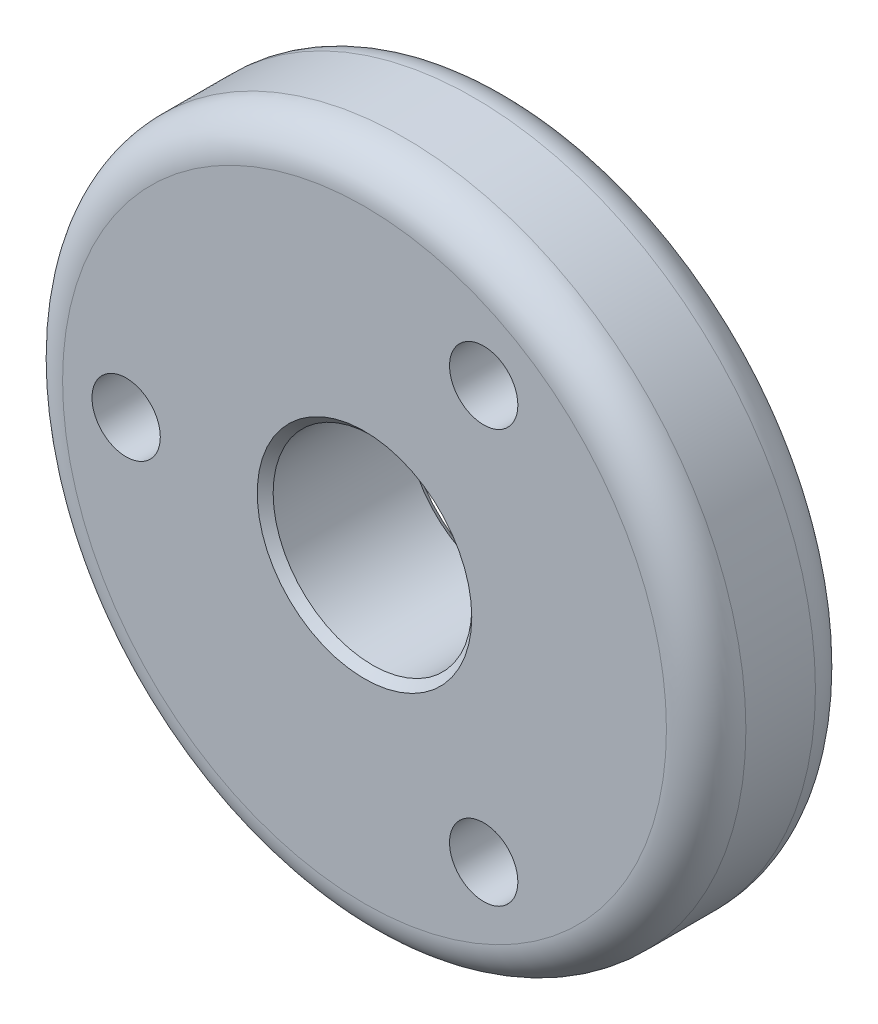
SolidWorks part; units mm, degrees
material "Alloy Steel"
ref_plane "Front Plane" through (0, 0, 0) normal (0, 0, 1) x (1, 0, 0)
ref_plane "Top Plane" through (0, 0, 0) normal (0, 1, 0) x (1, 0, 0)
ref_plane "Right Plane" through (0, 0, 0) normal (1, 0, 0) x (0, 0, -1)
sketch "Sketch1" plane through (0, 0, 0) normal (0, 0, 1) x (1, 0, 0)
  circle A0 centre (0, 0) radius 1.5875
  circle A1 centre (0, 0) radius 5.461
  dimension "D1" = 3.175
  dimension "D2" = 10.922
extrude "Boss-Extrude1" add sketch "Sketch1" along normal mid plane 2.3813
fillet "Fillet1" radius 0.635 2 edges at (5.461, 0, -1.1906) (5.461, 0, 1.1906)
chamfer "Chamfer1" distance 0.127 angle 45 2 edges at (1.5875, 0, -1.1906) (1.5875, 0, 1.1906)
sketch "Sketch2" plane through (0, 0, 1.1906) normal (0, 0, 1) x (1, 0, 0)
  circle A0 centre (-3.81, 0) radius 0.5461
  dimension "D2" = 1.0922
  dimension "D1" = 3.81
extrude "Cut-Extrude1" cut sketch "Sketch2" against normal through all
pattern_circular "CirPattern1" count 3 over 360 about axis through (0, 0, 0) along (0, 0, 1) of "Cut-Extrude1"
